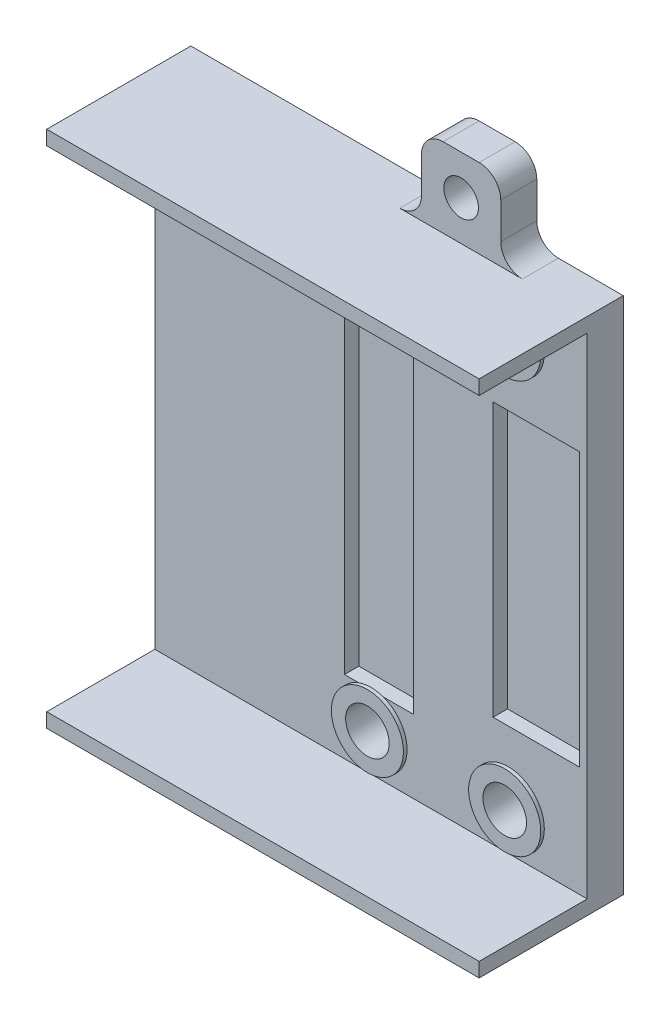
SolidWorks part; units mm, degrees
ref_plane "Front Plane" through (0, 0, 0) normal (0, 0, 1) x (1, 0, 0)
ref_plane "Top Plane" through (0, 0, 0) normal (0, 1, 0) x (1, 0, 0)
ref_plane "Right Plane" through (0, 0, 0) normal (1, 0, 0) x (0, 0, -1)
sketch "Sketch3" plane through (0, 0, 0) normal (0, 0, 1) x (1, 0, 0)
  line L1 (-30, 36) -> (30, 36)
  line L2 (-30, 36) -> (-30, -36)
  line L3 (-30, -36) -> (30, -36)
  line L4 (30, 36) -> (30, -36)
  line L5 (-30, 36) -> (30, -36) construction
  line L6 (-30, -36) -> (30, 36) construction
  point P0 (0, 0)
  dimension "D1" = 72
  dimension "D2" = 60
extrude "Boss-Extrude1" add sketch "Sketch3" along normal blind 5
sketch "Sketch5" plane through (0, 0, 5) normal (0, 0, 1) x (1, 0, 0)
  line L12 (30, -36) -> (30, 36)
  line L13 (30, 36) -> (-30, 36)
  line L14 (-30, 36) -> (-30, -36)
  line L15 (-30, -36) -> (30, -36)
  line L16 (30, -36) -> (30, 36) construction
  line L17 (30, 36) -> (-30, 36) construction
  line L18 (-30, 36) -> (-30, -36) construction
  line L19 (-30, -36) -> (30, -36) construction
  circle A0 centre (19.046, 28.575) radius 2.1 construction
  circle A21 centre (-0.004, -28.575) radius 2.1 construction
  circle A22 centre (19.046, -28.575) radius 2.1 construction
  circle A23 centre (19.046, 28.575) radius 2.1 construction
  circle A24 centre (19.046, 28.575) radius 3.025
  circle A25 centre (19.046, -28.575) radius 3.025
  circle A26 centre (-0.004, -28.575) radius 3.025
  circle A27 centre (-0.004, 28.575) radius 3.025
  circle A28 centre (19.046, 28.575) radius 5
  circle A29 centre (19.046, -28.575) radius 5
  circle A30 centre (-0.004, -28.575) radius 5
  circle A31 centre (-0.004, 28.575) radius 5
  dimension "D2" = 6.05
  dimension "D3" = 10
  dimension "D1" = 0
extrude "Boss-Extrude2" add sketch "Sketch5" along normal blind 0.5
sketch "Sketch6" plane through (0, 0, 5) normal (0, 0, 1) x (1, 0, 0)
  circle A0 centre (-0.004, 28.575) radius 3.025 construction
  circle A1 centre (19.046, 28.575) radius 3.025 construction
  circle A2 centre (-0.004, -28.575) radius 3.025 construction
  circle A3 centre (19.046, -28.575) radius 3.025 construction
  circle A4 centre (-0.004, 28.575) radius 3.025
  circle A5 centre (19.046, 28.575) radius 3.025
  circle A6 centre (-0.004, -28.575) radius 3.025
  circle A7 centre (19.046, -28.575) radius 3.025
extrude "Cut-Extrude1" cut sketch "Sketch6" against normal blind 4.5
sketch "Sketch8" plane through (0, 0, 5) normal (0, 0, 1) x (1, 0, 0)
  line L1 (-3.69, 23.528) -> (5.91, 23.528)
  line L2 (-3.69, 23.528) -> (-3.69, -23.872)
  line L3 (-3.69, -23.872) -> (5.91, -23.872)
  line L4 (5.91, 23.528) -> (5.91, -23.872)
  line L10 (21.633, -18.696) -> (16.933, -18.696) construction
  line L11 (16.933, 19.204) -> (28.933, 19.204)
  line L13 (16.933, -18.696) -> (28.933, -18.696)
  line L14 (28.933, 19.204) -> (28.933, -18.696)
  line L15 (16.933, -18.696) -> (16.933, -17.796) construction
  line L16 (16.933, 19.204) -> (16.933, -18.696)
  dimension "D1" = 12
extrude "Cut-Extrude2" cut sketch "Sketch8" against normal blind 2
sketch "Sketch10" plane through (0, 0, 5) normal (0, 0, 1) x (1, 0, 0)
  line L0 (30, -36) -> (30, 36) construction
  line L1 (-30, 36) -> (30, 36)
  line L2 (-30, 36) -> (-30, 34)
  line L3 (-30, 34) -> (30, 34)
  line L4 (30, 36) -> (30, 34)
  line L6 (-30, -36) -> (30, -36)
  line L7 (-30, -36) -> (-30, -34)
  line L8 (-30, -34) -> (30, -34)
  line L9 (30, -36) -> (30, -34)
  dimension "D1" = 2
extrude "Boss-Extrude3" add sketch "Sketch10" along normal blind 15
sketch "Sketch11" plane through (0, 0, 0) normal (0, 0, -1) x (-1, 0, 0)
  line L0 (-30, 36) -> (30, 36) construction
  line L1 (-18, 36) -> (-7, 36)
  line L2 (-18, 36) -> (-18, 47)
  line L3 (-18, 47) -> (-7, 47)
  line L4 (-7, 36) -> (-7, 47)
  line L5 (-12.5, 36) -> (-12.5, 47)
  line L6 (-30, 34) -> (-30, 36) construction
  circle A0 centre (-12.5, 41.5) radius 2 construction
  line M7 (30, 36) -> (-30, 36)
  dimension "D1" = 4
  dimension "D2" = 11
  dimension "D3" = 11
  dimension "D4" = 12
extrude "Boss-Extrude4" add sketch "Sketch11" against normal blind 5 contours L1 L5 L3 L2 | L5 L4 L3 M7
hole_wizard "M4 Clearance Hole1" positions "Sketch14" profile "Sketch13" hole size "M4" standard "ANSI Metric" end condition through all
sketch "Sketch14" plane through (0, 0, 5) normal (0, 0, 1) x (1, 0, 0)
  point P0 (12.5, 41.5)
sketch "Sketch13" plane through (12.5, 41.5, 5) normal (1, 0, 0) x (0, -1, 0)
  line L0 (0, 0) -> (0, 5)
  line L1 (0, 5) -> (2.4, 5)
  line L2 (2.4, 5) -> (2.4, 0)
  line L5 (2.4, 0) -> (0, 0)
  line L11 (0, -6.35) -> (0, 107.95) construction
  dimension "Thru Hole Dia." = 4.8
  dimension "Thru Hole Depth" = 5
mirror "Mirror1" about plane through (0, 0, 0) normal (0, 1, 0) of "Boss-Extrude4", "M4 Clearance Hole1"
fillet "Fillet2" radius 3 8 edges at (7, -36, 2.5) (7, -47, 2.5) (18, -47, 2.5) (18, -36, 2.5) (18, 47, 2.5) (18, 36, 2.5) (7, 47, 2.5) (7, 36, 2.5)
